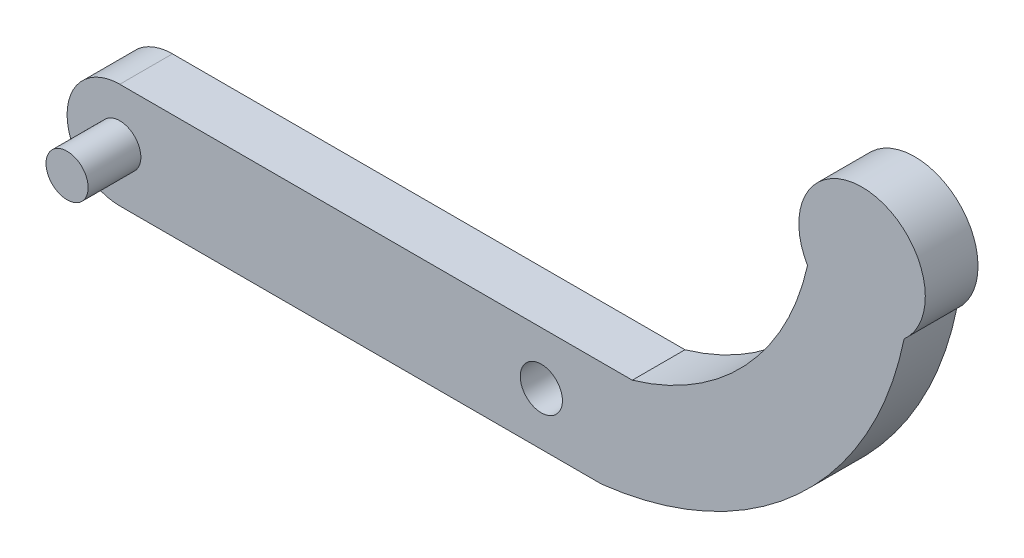
SolidWorks part; units mm, degrees
ref_plane "Alzado" through (0, 0, 0) normal (0, 0, 1) x (1, 0, 0)
ref_plane "Planta" through (0, 0, 0) normal (0, 1, 0) x (1, 0, 0)
ref_plane "Vista lateral" through (0, 0, 0) normal (1, 0, 0) x (0, 0, -1)
sketch "Croquis1" plane through (0, 0, 0) normal (0, 0, 1) x (1, 0, 0)
  line L0 (5.7883, -6.7404) -> (-39.9369, -6.7404)
  line L1 (8.6949, 3.2596) -> (-39.9369, 3.2596)
  arc A0 (-39.9369, -6.7404) -> (-39.9369, 3.2596) centre (-39.9369, -1.7404) cw
  arc A1 (25.3199, 20.9961) -> (8.6949, 3.2596) centre (2.0337, 26.1633) cw
  arc A2 (25.3199, 20.9961) -> (34.4825, 19.5431) centre (30.4973, 24.0285) cw
  arc A3 (34.4825, 19.5431) -> (5.7883, -6.7404) centre (2.0337, 26.1633) cw
extrude "Saliente-Extruir1" add sketch "Croquis1" along normal blind 5
sketch "Croquis2" plane through (0, 0, 0) normal (0, 0, -1) x (-1, 0, 0)
  circle A0 centre (39.9369, -1.7404) radius 2
  dimension "D2" = 4
extrude "Saliente-Extruir2" add sketch "Croquis2" against normal blind 10 contours A0
sketch "Croquis4" plane through (0, 0, 5) normal (0, 0, 1) x (1, 0, 0)
  line L0 (-39.9369, -1.7404) -> (0.0631, -1.7404) construction
  circle A0 centre (0.0631, -1.7404) radius 2
  dimension "D1" = 4
extrude "Cortar-Extruir1" cut sketch "Croquis4" against normal blind 10
